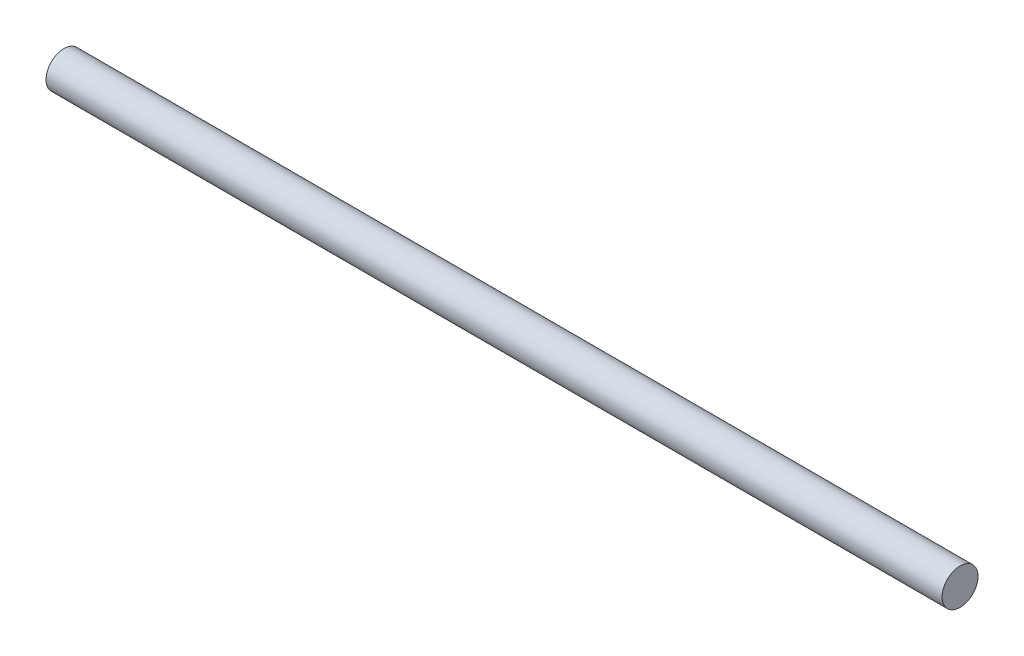
SolidWorks part; units mm, degrees
ref_plane "Front Plane" through (0, 0, 0) normal (0, 0, 1) x (1, 0, 0)
ref_plane "Top Plane" through (0, 0, 0) normal (0, 1, 0) x (1, 0, 0)
ref_plane "Right Plane" through (0, 0, 0) normal (1, 0, 0) x (0, 0, -1)
sketch "Sketch1" plane through (0, 0, 0) normal (1, 0, 0) x (0, 0, -1)
  circle A0 centre (0, 0) radius 19.05
  dimension "D1" = 38.1
extrude "Boss-Extrude1" add sketch "Sketch1" along normal blind 949.96
sketch "Sketch2" plane through (0, 0, 0) normal (0, 0, 1) x (1, 0, 0)
  line L0 (949.96, 19.05) -> (0, 19.05) construction
  point P0 (474.98, 19.05)
